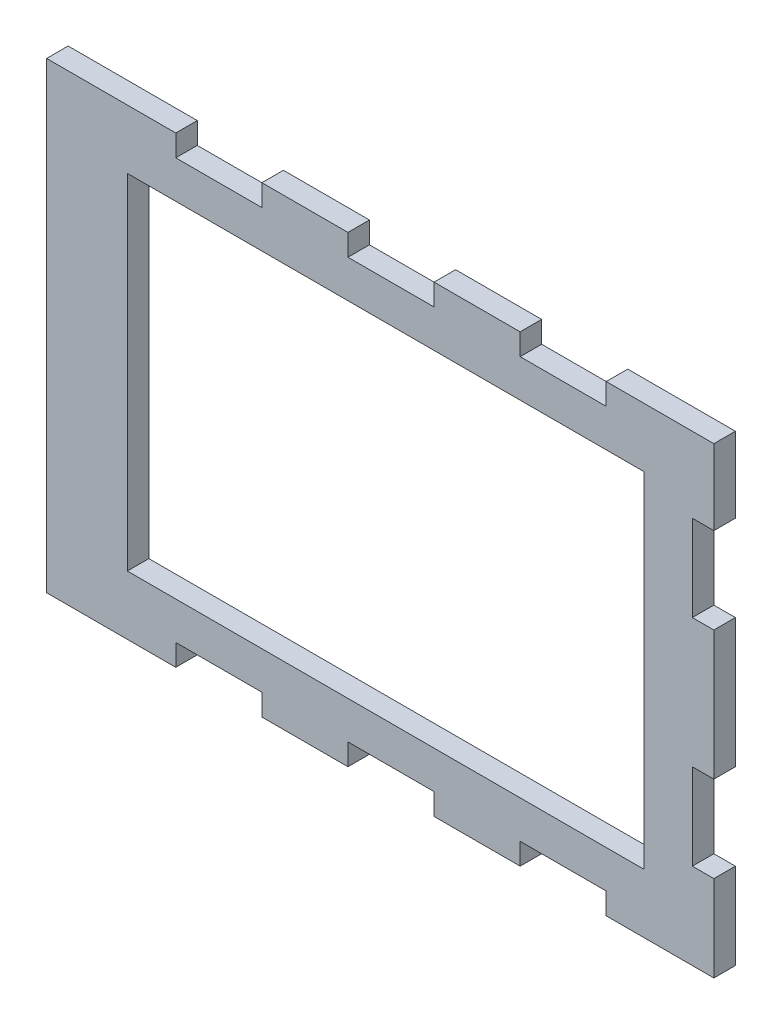
SolidWorks part; units mm, degrees
ref_plane "Front Plane" through (0, 0, 0) normal (0, 0, 1) x (1, 0, 0)
ref_plane "Top Plane" through (0, 0, 0) normal (0, 1, 0) x (1, 0, 0)
ref_plane "Right Plane" through (0, 0, 0) normal (1, 0, 0) x (0, 0, -1)
sketch "Sketch1" plane through (0, 0, 0) normal (0, 0, 1) x (1, 0, 0)
  line L1 (65.2195, -7.9375) -> (-131.6305, -7.9375)
  line L2 (65.2195, -7.9375) -> (65.2195, -144.4625)
  line L3 (65.2195, -144.4625) -> (-131.6305, -144.4625)
  line L4 (-131.6305, -7.9375) -> (-131.6305, -144.4625)
extrude "Boss-Extrude1" add sketch "Sketch1" along normal blind 6.35
sketch "Sketch2" plane through (0, 0, 6.35) normal (0, 0, 1) x (1, 0, 0)
  line L0 (-91.2922, -76.2) -> (25.6431, -76.2) construction
  line L1 (44.582, -25.4) -> (-107.818, -25.4)
  line L2 (44.582, -25.4) -> (44.582, -127)
  line L3 (44.582, -127) -> (-107.818, -127)
  line L4 (-107.818, -25.4) -> (-107.818, -127)
  line L5 (-131.6305, -144.4625) -> (65.2195, -144.4625) construction
  line L6 (65.2195, -7.9375) -> (-131.6305, -7.9375) construction
  line L7 (-131.6305, -7.9375) -> (-131.6305, -144.4625) construction
  dimension "D1" = 101.6
  dimension "D2" = 152.4
  dimension "D3" = 23.8125
extrude "Cut-Extrude1" cut sketch "Sketch2" against normal through all
sketch "Sketch3" plane through (0, 0, 0) normal (0, 0, -1) x (-1, 0, 0)
  line L0 (-65.2195, -144.4625) -> (-65.2195, -7.9375) construction
  line L1 (-58.8695, -93.6625) -> (-65.2195, -93.6625)
  line L2 (-58.8695, -93.6625) -> (-58.8695, -119.0625)
  line L3 (-58.8695, -119.0625) -> (-65.2195, -119.0625)
  line L4 (-65.2195, -93.6625) -> (-65.2195, -119.0625)
  line L5 (-65.2195, -119.0625) -> (-58.8695, -119.0625) construction
  line L6 (-65.2195, -7.9375) -> (131.6305, -7.9375) construction
  line L7 (-58.8695, -30.1625) -> (-65.2195, -30.1625)
  line L8 (-58.8695, -30.1625) -> (-58.8695, -55.5438)
  line L9 (-58.8695, -55.5438) -> (-65.2195, -55.5438)
  line L10 (-65.2195, -30.1625) -> (-65.2195, -55.5438)
  line L11 (-33.4695, -14.2875) -> (-8.0695, -14.2875)
  line L12 (-33.4695, -14.2875) -> (-33.4695, -7.9375)
  line L13 (-33.4695, -7.9375) -> (-8.0695, -7.9375)
  line L14 (-8.0695, -14.2875) -> (-8.0695, -7.9375)
  line L15 (-8.0695, -14.2875) -> (-8.0695, -7.9375) construction
  line L16 (42.7305, -14.2875) -> (42.7305, -7.9375) construction
  line L17 (17.3305, -14.2875) -> (42.7305, -14.2875)
  line L18 (17.3305, -14.2875) -> (17.3305, -7.9375)
  line L19 (17.3305, -7.9375) -> (42.7305, -7.9375)
  line L20 (42.7305, -14.2875) -> (42.7305, -7.9375)
  line L21 (93.5305, -14.2875) -> (93.5305, -7.9375) construction
  line L22 (68.1305, -14.2875) -> (93.5305, -14.2875)
  line L23 (68.1305, -14.2875) -> (68.1305, -7.9375)
  line L24 (68.1305, -7.9375) -> (93.5305, -7.9375)
  line L25 (93.5305, -14.2875) -> (93.5305, -7.9375)
  line L26 (131.6305, -144.4625) -> (-65.2195, -144.4625) construction
  line L27 (-33.4695, -138.1125) -> (-8.0695, -138.1125)
  line L28 (-33.4695, -138.1125) -> (-33.4695, -144.4625)
  line L29 (-33.4695, -144.4625) -> (-8.0695, -144.4625)
  line L30 (-8.0695, -138.1125) -> (-8.0695, -144.4625)
  line L32 (17.3305, -138.1125) -> (42.7305, -138.1125)
  line L33 (17.3305, -138.1125) -> (17.3305, -144.4625)
  line L34 (17.3305, -144.4625) -> (42.7305, -144.4625)
  line L35 (42.7305, -138.1125) -> (42.7305, -144.4625)
  line L36 (68.1305, -138.1125) -> (93.5305, -138.1125)
  line L37 (68.1305, -138.1125) -> (68.1305, -144.4625)
  line L38 (68.1305, -144.4625) -> (93.5305, -144.4625)
  line L39 (93.5305, -138.1125) -> (93.5305, -144.4625)
extrude "Cut-Extrude2" cut sketch "Sketch3" against normal blind 6.35
